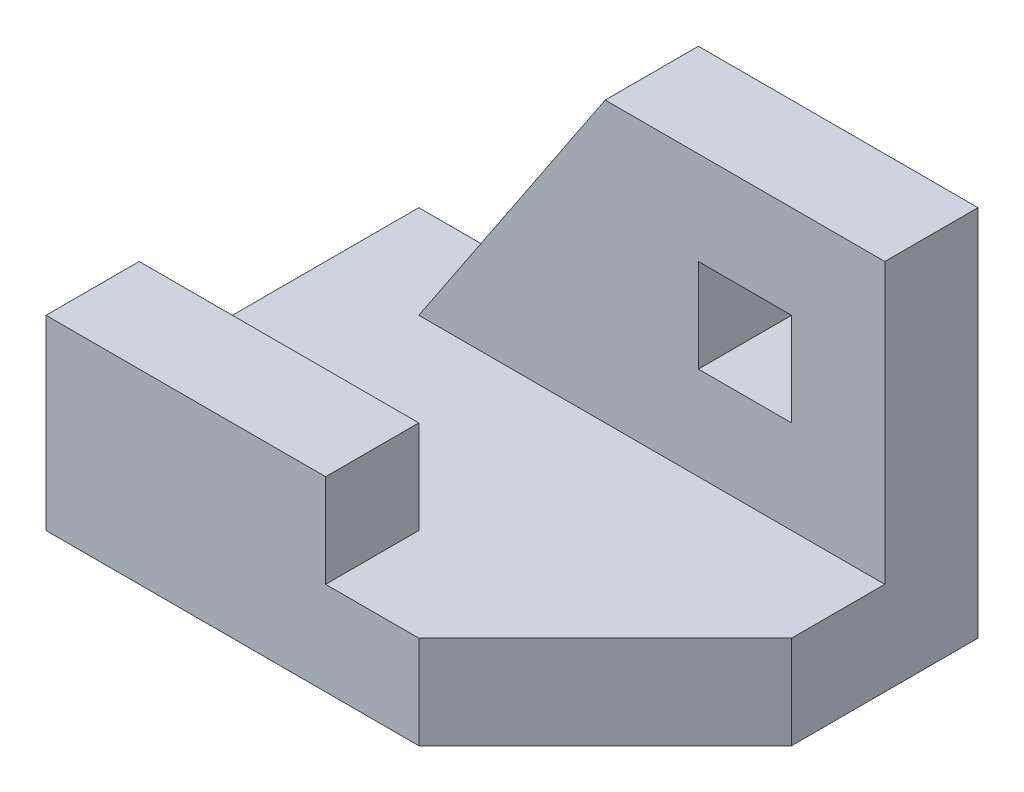
SolidWorks part; units mm, degrees
ref_plane "前基準面" through (0, 0, 0) normal (0, 0, 1) x (1, 0, 0)
ref_plane "上基準面" through (0, 0, 0) normal (0, 1, 0) x (1, 0, 0)
ref_plane "右基準面" through (0, 0, 0) normal (1, 0, 0) x (0, 0, -1)
sketch "草圖1" plane through (0, 0, 0) normal (0, 1, 0) x (1, 0, 0)
  line L0 (30, 10) -> (20, 0)
  line L1 (0, 0) -> (20, 0)
  line L2 (0, 0) -> (0, 20)
  line L3 (0, 20) -> (20, 20)
  line L4 (20, 0) -> (20, 20)
  line L5 (20, 20) -> (30, 20)
  line L6 (20, 20) -> (20, 10)
  line L7 (20, 10) -> (30, 10)
  line L8 (30, 20) -> (30, 10)
  point P8 (0, 0)
  point P9 (30, 15)
  point P10 (30, 11.3518)
  dimension "D1" = 20
  dimension "D2" = 20
  dimension "D3" = 30
  dimension "D4" = 10
  dimension "D5" = 10
extrude "填料-伸長1" add sketch "草圖1" along normal blind 5 contours L1 L4 L3 L2 | L7 L4 L0 | L8 L5 L4 L7
sketch "草圖2" plane through (0, 0, -20) normal (0, 0, -1) x (-1, 0, 0)
  line L0 (-30, 5) -> (-30, 20)
  line L1 (-30, 20) -> (-15, 20)
  line L2 (-15, 20) -> (-5, 5)
  line L3 (0, 5) -> (-30, 5) construction
  line L4 (-5, 5) -> (-30, 5)
  line L5 (0, 5) -> (0, 0) construction
  line L7 (-25, 15) -> (-20, 15)
  line L8 (-25, 15) -> (-25, 10)
  line L9 (-25, 10) -> (-20, 10)
  line L10 (-20, 15) -> (-20, 10)
  dimension "D1" = 15
  dimension "D2" = 15
  dimension "D3" = 5
  dimension "D4" = 5
  dimension "D5" = 5
  dimension "D6" = 5
extrude "填料-伸長2" add sketch "草圖2" against normal blind 5
sketch "草圖3" plane through (0, 5, 0) normal (0, 1, 0) x (1, 0, 0)
  line L1 (0, 0) -> (15, 0)
  line L2 (0, 0) -> (0, 5)
  line L3 (0, 5) -> (15, 5)
  line L4 (15, 0) -> (15, 5)
  dimension "D1" = 5
  dimension "D2" = 15
extrude "填料-伸長3" add sketch "草圖3" along normal blind 5
